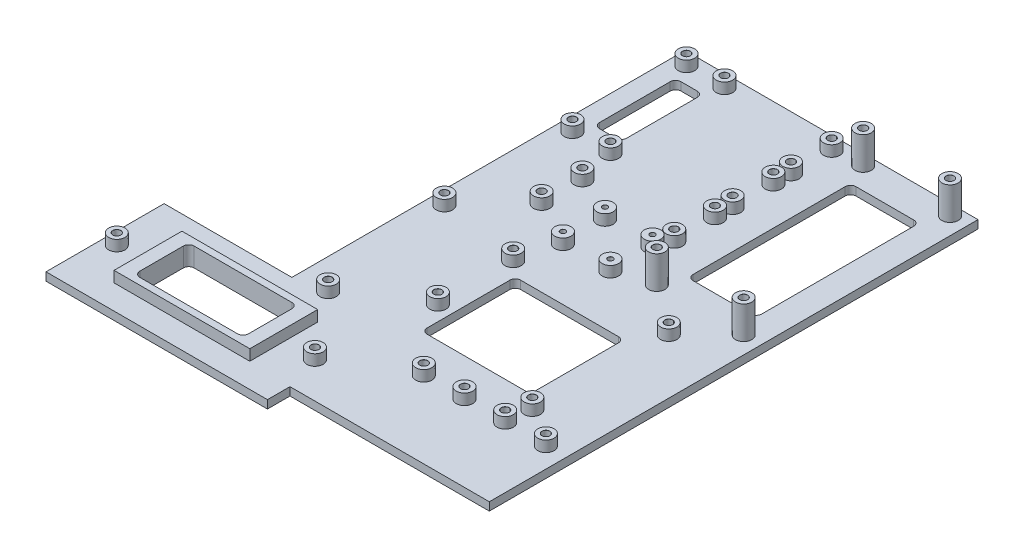
SolidWorks part; units mm, degrees
ref_plane "Front Plane" through (0, 0, 0) normal (0, 0, 1) x (1, 0, 0)
ref_plane "Top Plane" through (0, 0, 0) normal (0, 1, 0) x (1, 0, 0)
ref_plane "Right Plane" through (0, 0, 0) normal (1, 0, 0) x (0, 0, -1)
sketch "Sketch1" plane through (0, 0, 0) normal (0, 1, 0) x (1, 0, 0)
  line L1 (-77.5, 90) -> (77.5, 90)
  line L2 (-77.5, 90) -> (-77.5, -90)
  line L3 (-77.5, -90) -> (77.5, -90)
  line L4 (77.5, 90) -> (77.5, -90)
  line L5 (-77.5, 90) -> (77.5, -90) construction
  line L6 (-77.5, -90) -> (77.5, 90) construction
  point P0 (0, 0)
  dimension "D1" = 180
  dimension "D2" = 155
extrude "Boss-Extrude1" add sketch "Sketch1" along normal blind 1
sketch "Sketch2" plane through (0, 1, 0) normal (0, 1, 0) x (1, 0, 0)
  line L0 (-3.93, -57.795) -> (-68.93, -57.795) construction
  line L1 (-77.5, 90) -> (-30.43, 90)
  line L2 (-77.5, 90) -> (-77.5, -54.795)
  line L3 (-77.5, -54.795) -> (-30.43, -54.795)
  line L4 (-30.43, 90) -> (-30.43, -54.795)
  line L5 (-27.43, 32.205) -> (-27.43, 12.205) construction
  dimension "D1" = 3
  dimension "D2" = 3
extrude "Cut-Extrude1" cut sketch "Sketch2" against normal blind 1
sketch "Sketch3" plane through (0, 1, 0) normal (0, 1, 0) x (1, 0, 0)
  line L7 (-77.5, -90) -> (4.07, -90)
  line L8 (-77.5, -90) -> (-77.5, -98.295)
  line L9 (-77.5, -98.295) -> (4.07, -98.295)
  line L10 (4.07, -90) -> (4.07, -98.295)
  line L11 (-68.93, -95.795) -> (-3.93, -95.795) construction
  line L12 (-3.93, -95.795) -> (-3.93, -57.795) construction
  dimension "D3" = 2.5
  dimension "D4" = 8
extrude "Boss-Extrude2" add sketch "Sketch3" against normal blind 1
sketch "Sketch4" plane through (0, 1, 0) normal (0, 1, 0) x (1, 0, 0)
  circle A0 centre (-25.18, 85.295) radius 3
  circle A1 centre (-11.18, 85.295) radius 3
  circle A2 centre (-11.18, 43.295) radius 3
  circle A3 centre (-25.18, 43.295) radius 3
  circle A10 centre (-7.93, 29.705) radius 3
  circle A11 centre (-7.93, 14.705) radius 3
  circle A12 centre (0.07, -76.795) radius 3
  circle A13 centre (-72.93, -76.795) radius 3
  circle A14 centre (25.15, -61.795) radius 3
  circle A15 centre (40.15, -61.795) radius 3
  circle A16 centre (55.15, -61.795) radius 3
  circle A17 centre (70.15, -61.795) radius 3
  circle A18 centre (5.1, -8.805) radius 3
  circle A19 centre (5.1, -36.555) radius 3
  circle A20 centre (56.1, -52.755) radius 3
  circle A21 centre (57.3, -3.705) radius 3
  circle A22 centre (26.32, 5.795) radius 3
  circle A23 centre (8.82, 5.795) radius 3
  circle A24 centre (8.82, 21.295) radius 3
  circle A25 centre (26.32, 21.295) radius 3
  circle A26 centre (28.57, 27.045) radius 3
  circle A27 centre (28.57, 42.045) radius 3
  circle A28 centre (28.57, 48.545) radius 3
  circle A29 centre (28.57, 63.545) radius 3
  circle A30 centre (28.57, 70.045) radius 3
  circle A31 centre (28.57, 85.045) radius 3
  circle A32 centre (39.15, 86.045) radius 3
  circle A33 centre (71.15, 86.045) radius 3
  circle A34 centre (71.15, 10.045) radius 3
  circle A35 centre (39.15, 10.045) radius 3
  circle A36 centre (-25.35, -3.705) radius 3
  circle A37 centre (-19.1, -52.755) radius 3
  point P12 (5.1, -8.805)
  point P13 (59.18, -3.995)
  point P15 (57.3, -3.705)
  point P16 (56.1, -52.755)
  point P18 (5.1, -36.555)
  point P22 (-25.35, -3.705)
  point P27 (-19.1, -52.755)
  dimension "D1" = 6
extrude "Boss-Extrude3" add sketch "Sketch4" along normal blind 4
sketch "Sketch5" plane through (0, 5, 0) normal (0, 1, 0) x (1, 0, 0)
  circle A0 centre (39.15, 86.045) radius 3 construction
  circle A1 centre (71.15, 10.045) radius 3
  circle A2 centre (71.15, 10.045) radius 3
  circle A3 centre (39.15, 10.045) radius 3
  circle A4 centre (39.15, 10.045) radius 3
  circle A5 centre (71.15, 86.045) radius 3 construction
  circle A6 centre (39.15, 86.045) radius 3
  circle A7 centre (71.15, 86.045) radius 3
  dimension "D1" = 0
  dimension "D2" = 0
extrude "Boss-Extrude4" add sketch "Sketch5" along normal blind 8
sketch "Sketch6" plane through (0, 0, 0) normal (0, -1, 0) x (1, 0, 0)
  line L6 (-30.43, 54.795) -> (-30.43, -90)
  line L8 (-77.5, 54.795) -> (-30.43, 54.795)
  line L12 (-30.43, -90) -> (77.5, -90)
  line L13 (77.5, -90) -> (77.5, 90)
  line L14 (77.5, 90) -> (4.07, 90)
  line L15 (-77.5, 98.295) -> (-77.5, 54.795)
  line L16 (-77.5, 54.795) -> (-30.43, 54.795)
  line L20 (-30.43, -90) -> (77.5, -90)
  line L21 (77.5, -90) -> (77.5, 90)
  line L22 (77.5, 90) -> (4.07, 90)
  line L23 (-77.5, 98.295) -> (-77.5, 54.795)
  line L28 (-30.43, 54.795) -> (-30.43, -90)
  line L32 (4.07, 90) -> (4.07, 98.295)
  line L34 (4.07, 90) -> (4.07, 98.295)
  line L36 (4.07, 98.295) -> (-77.5, 98.295)
  line L38 (4.07, 98.295) -> (-77.5, 98.295)
  dimension "D1" = 0
extrude "Boss-Extrude5" add sketch "Sketch6" along normal blind 2
hole_wizard "Ø2.9 (2.9) Diameter Hole2" positions "Sketch11" profile "Sketch12" hole size "Ø2.9" standard "ISO"
sketch "Sketch11" plane through (0, 5, 0) normal (0, 1, 0) x (1, 0, 0)
  point P12 (25.15, -61.795)
  point P15 (40.15, -61.795)
  point P18 (55.15, -61.795)
  point P21 (70.15, -61.795)
  point P27 (57.3, -3.705)
  point P54 (-11.18, 43.295)
  point P57 (-25.18, 43.295)
  point P60 (-11.18, 85.295)
  point P63 (-25.18, 85.295)
  point P69 (28.57, 85.045)
  point P72 (28.57, 70.045)
  point P75 (28.57, 63.545)
  point P78 (28.57, 48.545)
  point P81 (28.57, 42.045)
  point P84 (28.57, 27.045)
  point P90 (0.07, -76.795)
  point P93 (-72.93, -76.795)
  point P99 (-19.1, -52.755)
  point P102 (-25.35, -3.705)
  point P105 (57.3, -3.705)
  point P108 (56.1, -52.755)
  point P112 (39.15, 86.045)
  point P115 (39.15, 10.045)
  point P118 (71.15, 10.045)
  point P121 (71.15, 86.045)
  point P125 (-7.93, 29.705)
  point P128 (-7.93, 14.705)
  point P135 (5.1, -8.805)
  point P138 (5.1, -36.555)
  point P142 (0, 0)
sketch "Sketch12" plane through (25.15, 5, 61.795) normal (1, 0, 0) x (0, 0, 1)
  line L0 (0, 0) -> (0, 7)
  line L1 (0, 7) -> (1.45, 7)
  line L2 (1.45, 7) -> (1.45, 0.025)
  line L3 (1.45, 0.025) -> (1.475, 0)
  line L5 (1.475, 0) -> (0, 0)
  line L6 (-1.45, 0.025) -> (-1.475, 0) construction
  line L11 (0, -6.35) -> (0, 107.95) construction
  dimension "Thru Hole Dia." = 2.9
  dimension "Thru Hole Depth" = 7
  dimension "Near C'Sink Dia." = 2.95
  dimension "Near C'Sink Angle" = 90
hole_wizard "Ø1.9 (1.9) Diameter Hole1" positions "Sketch13" profile "Sketch14" hole size "Ø1.9" standard "ISO" end condition through all
sketch "Sketch13" plane through (0, 5, 0) normal (0, 1, 0) x (1, 0, 0)
  point P0 (8.82, 21.295)
  point P3 (26.32, 21.295)
  point P6 (26.32, 5.795)
  point P9 (8.82, 5.795)
sketch "Sketch14" plane through (8.82, 5, -21.295) normal (1, 0, 0) x (0, 0, 1)
  line L0 (0, 0) -> (0, 7)
  line L1 (0, 7) -> (0.95, 7)
  line L2 (0.95, 7) -> (0.95, 0.025)
  line L3 (0.95, 0.025) -> (0.975, 0)
  line L5 (0.975, 0) -> (0, 0)
  line L6 (-0.95, 0.025) -> (-0.975, 0) construction
  line L11 (0, -6.35) -> (0, 107.95) construction
  dimension "Thru Hole Dia." = 1.9
  dimension "Thru Hole Depth" = 7
  dimension "Near C'Sink Dia." = 1.95
  dimension "Near C'Sink Angle" = 90
hole_wizard "Ø2.9 (2.9) Diameter Hole1" positions "Sketch15" profile "Sketch16" hole size "Ø2.9" standard "ISO" end condition through all
sketch "Sketch15" plane through (0, 13, 0) normal (0, 1, 0) x (1, 0, 0)
  point P0 (71.15, 86.045)
  point P3 (39.15, 86.045)
  point P6 (39.15, 10.045)
  point P9 (71.15, 10.045)
sketch "Sketch16" plane through (71.15, 13, -86.045) normal (1, 0, 0) x (0, 0, 1)
  line L0 (0, 0) -> (0, 15)
  line L1 (0, 15) -> (1.45, 15)
  line L2 (1.45, 15) -> (1.45, 0.025)
  line L3 (1.45, 0.025) -> (1.475, 0)
  line L5 (1.475, 0) -> (0, 0)
  line L6 (-1.45, 0.025) -> (-1.475, 0) construction
  line L11 (0, -6.35) -> (0, 107.95) construction
  dimension "Thru Hole Dia." = 2.9
  dimension "Thru Hole Depth" = 15
  dimension "Near C'Sink Dia." = 2.95
  dimension "Near C'Sink Angle" = 90
sketch "Sketch18" plane through (0, 1, 0) normal (0, 1, 0) x (1, 0, 0)
  line L0 (-72.93, -76.795) -> (0.07, -76.795) construction
  line L1 (5.1, -8.805) -> (56.1, -52.755) construction
  line L7 (-56.43, -66.795) -> (-16.43, -66.795)
  line L8 (39.15, 86.045) -> (71.15, 10.045) construction
  line L9 (10.6, -13.5447) -> (50.6, -13.5447)
  line L10 (10.6, -13.5447) -> (10.6, -48.0153)
  line L11 (10.6, -48.0153) -> (50.6, -48.0153)
  line L12 (50.6, -13.5447) -> (50.6, -48.0153)
  line L13 (10.6, -13.5447) -> (50.6, -48.0153) construction
  line L14 (10.6, -48.0153) -> (50.6, -13.5447) construction
  line L15 (-25.18, 85.295) -> (-11.18, 43.295) construction
  line L16 (42.5184, 78.045) -> (67.7816, 78.045)
  line L17 (42.5184, 78.045) -> (42.5184, 18.045)
  line L18 (42.5184, 18.045) -> (67.7816, 18.045)
  line L19 (67.7816, 78.045) -> (67.7816, 18.045)
  line L20 (42.5184, 78.045) -> (67.7816, 18.045) construction
  line L21 (42.5184, 18.045) -> (67.7816, 78.045) construction
  line L22 (-56.43, -66.795) -> (-56.43, -86.795)
  line L23 (-23.18, 79.295) -> (-13.18, 79.295)
  line L24 (-23.18, 79.295) -> (-23.18, 49.295)
  line L25 (-23.18, 49.295) -> (-13.18, 49.295)
  line L26 (-13.18, 79.295) -> (-13.18, 49.295)
  line L27 (-23.18, 79.295) -> (-13.18, 49.295) construction
  line L28 (-23.18, 49.295) -> (-13.18, 79.295) construction
  line L29 (-56.43, -86.795) -> (-16.43, -86.795)
  line L30 (-16.43, -66.795) -> (-16.43, -86.795)
  line L31 (-56.43, -66.795) -> (-16.43, -86.795) construction
  line L32 (-56.43, -86.795) -> (-16.43, -66.795) construction
  point P4 (-36.43, -76.795)
  point P13 (30.6, -30.78)
  point P22 (55.15, 48.045)
  point P31 (-18.18, 64.295)
  dimension "D1" = 40
  dimension "D2" = 20
  dimension "D3" = 40
  dimension "D4" = 60
  dimension "D5" = 30
extrude "Cut-Extrude2" cut sketch "Sketch18" against normal through all
fillet "Fillet1" radius 2 16 edges at (-23.18, -0.5, -49.295) (10.6, -0.5, 48.0153) (42.5184, -0.5, -18.045) (-13.18, -0.5, -49.295) (67.7816, -0.5, -18.045) (50.6, -0.5, 48.0153) (-16.43, -0.5, 86.795) (50.6, -0.5, 13.5447) (67.7816, -0.5, -78.045) (-13.18, -0.5, -79.295) (-23.18, -0.5, -79.295) (42.5184, -0.5, -78.045) (10.6, -0.5, 13.5447) (-56.43, -0.5, 86.795) (-16.43, -0.5, 66.795) (-56.43, -0.5, 66.795)
sketch "Sketch19" plane through (0, 1, 0) normal (0, 1, 0) x (1, 0, 0)
  line L12 (-72.93, -76.795) -> (0.07, -76.795) construction
  line L14 (-61.43, -64.295) -> (-11.43, -64.295)
  line L15 (-61.43, -64.295) -> (-61.43, -89.295)
  line L16 (-61.43, -89.295) -> (-11.43, -89.295)
  line L17 (-11.43, -64.295) -> (-11.43, -89.295)
  line L18 (-61.43, -64.295) -> (-11.43, -89.295) construction
  line L19 (-61.43, -89.295) -> (-11.43, -64.295) construction
  point P2 (-36.43, -76.795)
  dimension "D1" = 50
  dimension "D2" = 25
extrude "Boss-Extrude6" add sketch "Sketch19" along normal blind 4
sketch "Sketch20" plane through (0, 1, 0) normal (0, -1, 0) x (1, 0, 0)
  line L4 (-56.43, 84.795) -> (-56.43, 68.795)
  line L6 (-56.43, 84.795) -> (-56.43, 68.795)
  line L12 (-54.43, 66.795) -> (-18.43, 66.795)
  line L14 (-54.43, 66.795) -> (-18.43, 66.795)
  line L16 (-16.43, 68.795) -> (-16.43, 84.795)
  line L17 (-16.43, 68.795) -> (-16.43, 84.795)
  line L18 (-18.43, 86.795) -> (-54.43, 86.795)
  line L19 (-18.43, 86.795) -> (-54.43, 86.795)
  arc A4 (-56.43, 68.795) -> (-54.43, 66.795) centre (-54.43, 68.795) ccw
  arc A5 (-56.43, 68.795) -> (-54.43, 66.795) centre (-54.43, 68.795) ccw
  arc A6 (-18.43, 66.795) -> (-16.43, 68.795) centre (-18.43, 68.795) ccw
  arc A7 (-18.43, 66.795) -> (-16.43, 68.795) centre (-18.43, 68.795) ccw
  arc A12 (-16.43, 84.795) -> (-18.43, 86.795) centre (-18.43, 84.795) ccw
  arc A13 (-16.43, 84.795) -> (-18.43, 86.795) centre (-18.43, 84.795) ccw
  arc A14 (-54.43, 86.795) -> (-56.43, 84.795) centre (-54.43, 84.795) ccw
  arc A15 (-54.43, 86.795) -> (-56.43, 84.795) centre (-54.43, 84.795) ccw
  dimension "D1" = 0
extrude "Cut-Extrude3" cut sketch "Sketch20" against normal blind 10
